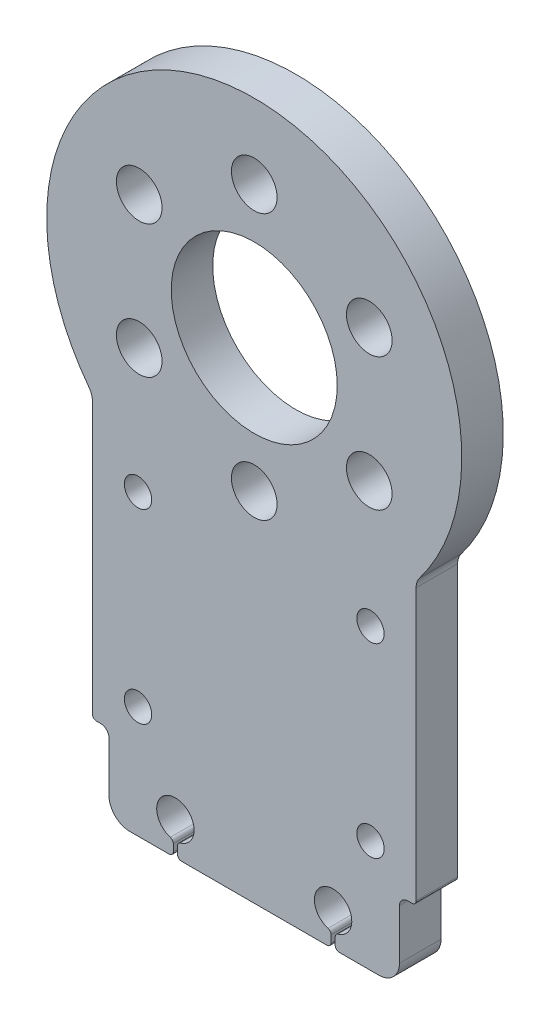
SolidWorks part; units mm, degrees
ref_plane "前视基准面" through (0, 0, 0) normal (0, 0, 1) x (1, 0, 0)
ref_plane "上视基准面" through (0, 0, 0) normal (0, 1, 0) x (1, 0, 0)
ref_plane "右视基准面" through (0, 0, 0) normal (1, 0, 0) x (0, 0, -1)
ref_plane "基准面1" through (0, 0, 0) normal (0, 0, -1) x (-1, 0, 0)
sketch "草图1" plane through (0, 0, 0) normal (0, 0, -1) x (-1, 0, 0)
  line L0 (-15, -59) -> (-10.25, -59)
  line L1 (-9.75, -58.5) -> (-9.75, -57.6458)
  line L2 (-9.25, -57.6458) -> (-9.25, -58.5)
  line L3 (-8.75, -59) -> (8.75, -59)
  line L4 (9.25, -58.5) -> (9.25, -57.6458)
  line L5 (9.75, -57.6458) -> (9.75, -58.5)
  line L6 (10.25, -59) -> (15, -59)
  line L7 (17.5, -56.5) -> (17.5, -50.5)
  line L8 (18.5, -49.5) -> (19, -49.5)
  line L9 (19.5, -49) -> (19.5, -16.3325)
  line L10 (-19.5, -16.3325) -> (-19.5, -49)
  line L11 (-19, -49.5) -> (-18.5, -49.5)
  line L12 (-17.5, -50.5) -> (-17.5, -56.5)
  circle A0 centre (0, 0) radius 10
  circle A1 centre (13.8564, 8) radius 2.75
  circle A2 centre (13.8564, -8) radius 2.75
  circle A3 centre (0, -16) radius 2.75
  circle A4 centre (-13.8564, -8) radius 2.75
  circle A5 centre (-13.8564, 8) radius 2.75
  circle A6 centre (0, 16) radius 2.75
  circle A7 centre (14, -23.0868) radius 1.65
  circle A8 centre (-14, -23.0868) radius 1.65
  circle A9 centre (-14, -45.5) radius 1.65
  circle A10 centre (14, -45.5) radius 1.65
  arc A11 (-10.25, -59) -> (-9.75, -58.5) centre (-10.25, -58.5) ccw
  arc A12 (-9.75, -57.6458) -> (-10.1136, -57.1647) centre (-10.25, -57.6458) ccw
  arc A13 (-10.1136, -57.1647) -> (-8.8864, -57.1647) centre (-9.5, -55) cw
  arc A14 (-8.8864, -57.1647) -> (-9.25, -57.6458) centre (-8.75, -57.6458) ccw
  arc A15 (-9.25, -58.5) -> (-8.75, -59) centre (-8.75, -58.5) ccw
  arc A16 (8.75, -59) -> (9.25, -58.5) centre (8.75, -58.5) ccw
  arc A17 (9.25, -57.6458) -> (8.8864, -57.1647) centre (8.75, -57.6458) ccw
  arc A18 (8.8864, -57.1647) -> (10.1136, -57.1647) centre (9.5, -55) cw
  arc A19 (10.1136, -57.1647) -> (9.75, -57.6458) centre (10.25, -57.6458) ccw
  arc A20 (9.75, -58.5) -> (10.25, -59) centre (10.25, -58.5) ccw
  arc A21 (15, -59) -> (17.5, -56.5) centre (15, -56.5) ccw
  arc A22 (17.5, -50.5) -> (18.5, -49.5) centre (18.5, -50.5) cw
  arc A23 (19, -49.5) -> (19.5, -49) centre (19, -49) ccw
  arc A24 (19.5, -16.3325) -> (19.9074, -15.1227) centre (21.5, -16.3325) cw
  arc A25 (19.9074, -15.1227) -> (-19.9074, -15.1227) centre (0, 0) ccw
  arc A26 (-19.9074, -15.1227) -> (-19.5, -16.3325) centre (-21.5, -16.3325) cw
  arc A27 (-19.5, -49) -> (-19, -49.5) centre (-19, -49) ccw
  arc A28 (-18.5, -49.5) -> (-17.5, -50.5) centre (-18.5, -50.5) cw
  arc A29 (-17.5, -56.5) -> (-15, -59) centre (-15, -56.5) ccw
extrude "凸台-拉伸1" add sketch "草图1" against normal blind 5
